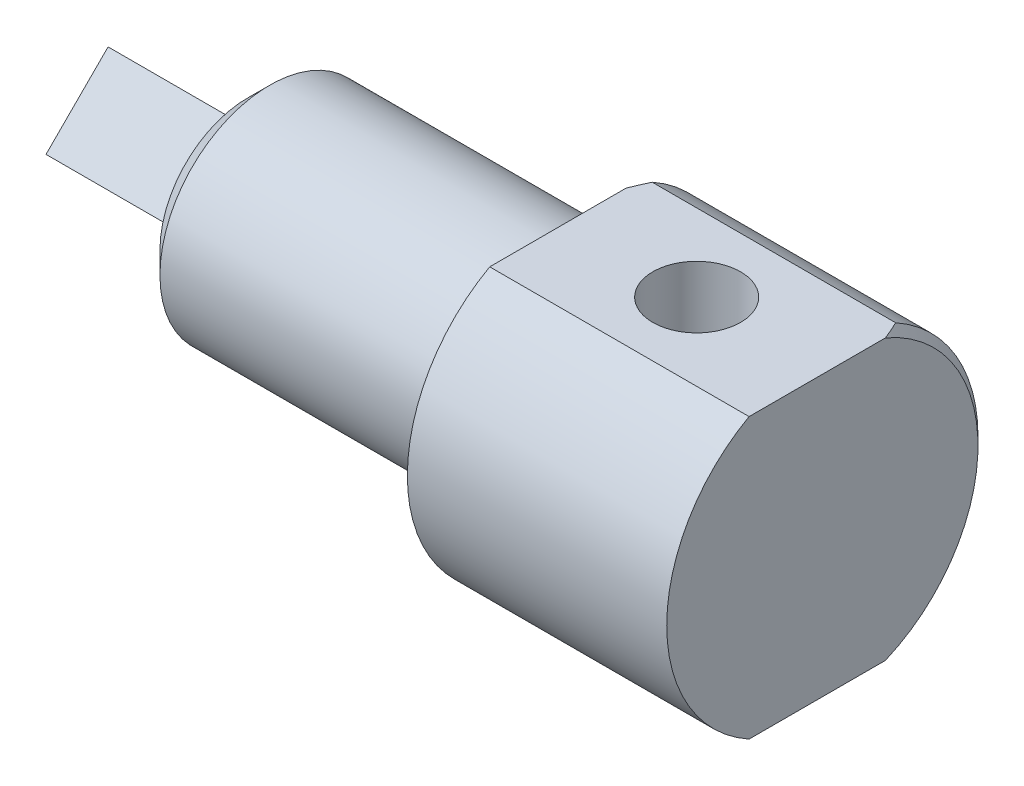
SolidWorks part; units mm, degrees
ref_plane "Спереди" through (0, 0, 0) normal (0, 0, 1) x (1, 0, 0)
ref_plane "Сверху" through (0, 0, 0) normal (0, 1, 0) x (1, 0, 0)
ref_plane "Справа" through (0, 0, 0) normal (1, 0, 0) x (0, 0, -1)
sketch "Эскиз1" plane through (0, 0, 0) normal (0, 0, 1) x (1, 0, 0)
  line L0 (0, 0) -> (-9.5781, 0) construction
  line L1 (0, 0) -> (0, 27.5)
  line L2 (0, 27.5) -> (80, 27.5)
  line L3 (80, 27.5) -> (80, 40)
  line L4 (80, 40) -> (145, 40)
  line L5 (145, 40) -> (145, 0)
  line L6 (145, 0) -> (0, 0)
  dimension "D1" = 145
  dimension "D2" = 80
  dimension "D3" = 80
  dimension "D4" = 55
revolve "Повернуть1" add sketch "Эскиз1" angle 360 about L0
sketch "Эскиз3" plane through (0, 0, 0) normal (-1, 0, 0) x (0, 0, 1)
  line L0 (0, 27.5) -> (0, -27.5) construction
  line L1 (-27.5, 0) -> (27.5, 0) construction
  line L2 (0, -15.5563) -> (-15.5563, 0)
  line L3 (0, -15.5563) -> (15.5563, 0)
  line L4 (-15.5563, 0) -> (0, 15.5563)
  line L5 (15.5563, 0) -> (0, 15.5563)
  line L6 (0, -15.5563) -> (0, 15.5563) construction
  line L7 (-15.5563, 0) -> (15.5563, 0) construction
  circle A0 centre (0, 0) radius 27.5 construction
  circle A1 centre (0, 0) radius 27.5 construction
  point P10 (0, 0)
  dimension "D1" = 22
extrude "Бобышка-Вытянуть1" add sketch "Эскиз3" along normal blind 35
sketch "Эскиз4" plane through (0, 0, 0) normal (0, 1, 0) x (1, 0, 0)
  line L0 (80, 27.5) -> (0, 27.5) construction
  line L1 (15, 27.5) -> (60, 27.5)
  line L2 (15, 27.5) -> (15, 22.5)
  line L3 (15, 22.5) -> (60, 22.5)
  line L4 (60, 27.5) -> (60, 22.5)
  line L6 (0, 27.5) -> (0, -27.5) construction
  dimension "D1" = 45
  dimension "D2" = 5
  dimension "D3" = 15
extrude "Вырез-Вытянуть1" cut sketch "Эскиз4" against normal mid plane 16
sketch "Эскиз5" plane through (145, 0, 0) normal (1, 0, 0) x (0, 0, -1)
  line L0 (-19.3649, 35) -> (19.3649, 35)
  line L1 (-40, 0) -> (40, 0) construction
  circle A0 centre (0, 0) radius 40 construction
  dimension "D1" = 70
extrude "Вырез-Вытянуть2" cut sketch "Эскиз5" against normal through all and the other way through all
mirror "Зеркальное отражение1" about plane through (0, 0, 0) normal (0, 1, 0) of "Вырез-Вытянуть2"
sketch "Эскиз6" plane through (0, 35, 0) normal (0, 1, 0) x (1, 0, 0)
  line L0 (80, 40) -> (80, 19.3649) construction
  line L1 (80, 0) -> (145, 0) construction
  line L2 (80, 27.5) -> (80, -27.5) construction
  line L3 (145, 19.3649) -> (145, -19.3649) construction
  circle A0 centre (112.5, 0) radius 11
  dimension "D2" = 22
  dimension "D1" = 32.5
extrude "Вырез-Вытянуть3" cut sketch "Эскиз6" against normal through all both and the other way through all
chamfer "Фаска1" distance 2 angle 45 2 edges at (145, 0, -40) (80, 0, -40)
chamfer "Фаска2" distance 5.5 angle 45 1 edges at (0, 0, -27.5)
